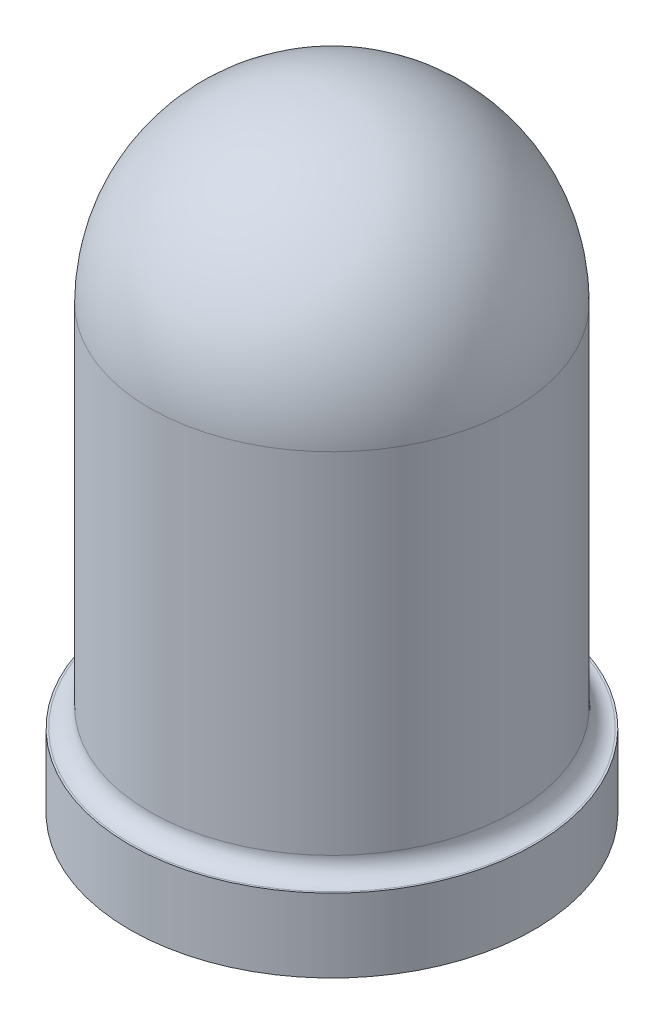
SolidWorks part; units mm, degrees
ref_plane "Front Plane" through (0, 0, 0) normal (0, 0, 1) x (1, 0, 0)
ref_plane "Top Plane" through (0, 0, 0) normal (0, 1, 0) x (1, 0, 0)
ref_plane "Right Plane" through (0, 0, 0) normal (1, 0, 0) x (0, 0, -1)
sketch "Sketch2" plane through (0, 0, 0) normal (1, 0, 0) x (0, 0, -1)
  line L4 (-2.475, 1.25) -> (-2.475, 6.005)
  line L5 (0, 13.1713) -> (0, 0)
  line L7 (0, 0) -> (-2.75, 0)
  line L8 (0, 0) -> (0, 1.6767)
  line L9 (-2.725, 1) -> (-2.75, 1)
  line L10 (-2.75, 0) -> (-2.75, 1)
  arc A1 (-2.475, 1.25) -> (-2.725, 1) centre (-2.725, 1.25) cw
  arc A2 (0, 8.48) -> (-2.475, 6.005) centre (0, 6.005) ccw
  point P13 (0, 0)
  point P14 (0, 0)
  point P15 (0, 0)
  dimension "D3" = 0.25
  dimension "D5" = 2.475
  dimension "D1" = 2.475
  dimension "D2" = 2.75
  dimension "D4" = 2.475
  dimension "D6" = 8.48
  dimension "D7" = 1
  dimension "D8" = 7.23
revolve "Revolve2" add sketch "Sketch2" angle 360 about L5
equation "\"D5@Sketch2\"=\"D4@Sketch2\""
